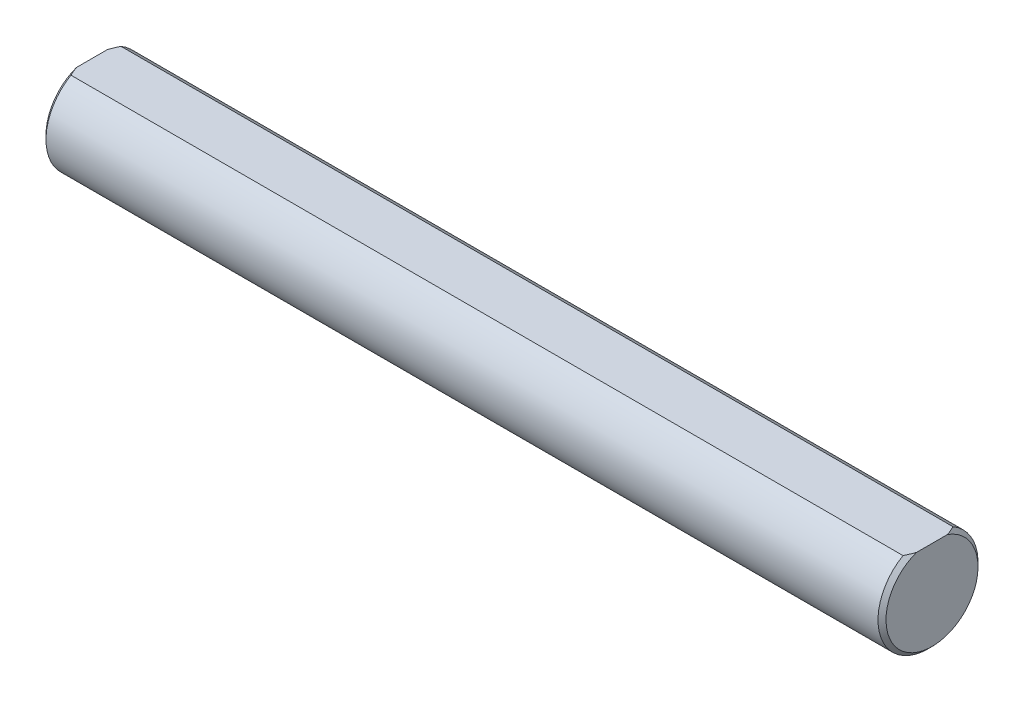
SolidWorks part; units mm, degrees
material "AISI 1045 Steel, cold drawn"
ref_plane "Front Plane" through (0, 0, 0) normal (0, 0, 1) x (1, 0, 0)
ref_plane "Top Plane" through (0, 0, 0) normal (0, 1, 0) x (1, 0, 0)
ref_plane "Right Plane" through (0, 0, 0) normal (1, 0, 0) x (0, 0, -1)
sketch "Sketch1" plane through (0, 0, 0) normal (1, 0, 0) x (0, 0, -1)
  circle A2 centre (0, 0) radius 3.175
  dimension "D1" = 6.35
extrude "Boss-Extrude1" add sketch "Sketch1" along normal blind 53.34
chamfer "Chamfer1" distance 0.254 angle 45 2 edges at (53.34, 0, -3.175) (0, 0, -3.175)
sketch "Sketch2" plane through (53.34, 0, 0) normal (1, 0, 0) x (0, 0, -1)
  line L0 (-1.5875, 2.7496) -> (1.5875, 2.7496)
  circle A0 centre (0, 0) radius 3.175 construction
  arc A1 (1.5875, 2.7496) -> (-1.5875, 2.7496) centre (0, 0) ccw
  dimension "D1" = 3.175
extrude "Cut-Extrude2" cut sketch "Sketch2" against normal through all
